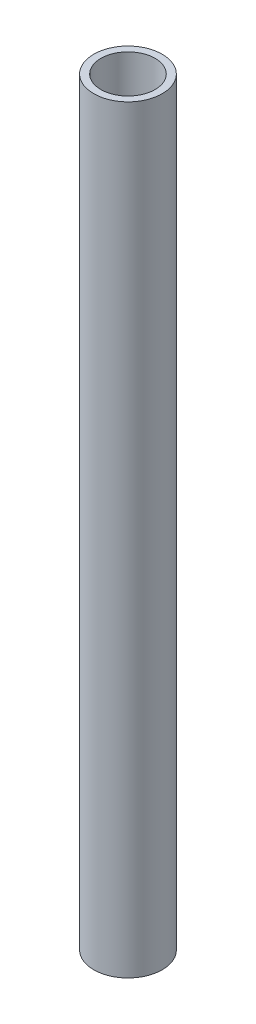
SolidWorks part; units mm, degrees
material "Cam"
ref_plane "Ön Düzlem" through (0, 0, 0) normal (0, 0, 1) x (1, 0, 0)
ref_plane "Üst Düzlem" through (0, 0, 0) normal (0, 1, 0) x (1, 0, 0)
ref_plane "Sağ Düzlem" through (0, 0, 0) normal (1, 0, 0) x (0, 0, -1)
sketch "Çizim1" plane through (0, 0, 0) normal (0, 1, 0) x (1, 0, 0)
  circle A0 centre (0, 0) radius 12
  circle A1 centre (0, 0) radius 9.5
  dimension "D1" = 24
  dimension "D2" = 19
extrude "Yükseklik-Ekstrüzyon1" add sketch "Çizim1" along normal blind 266
